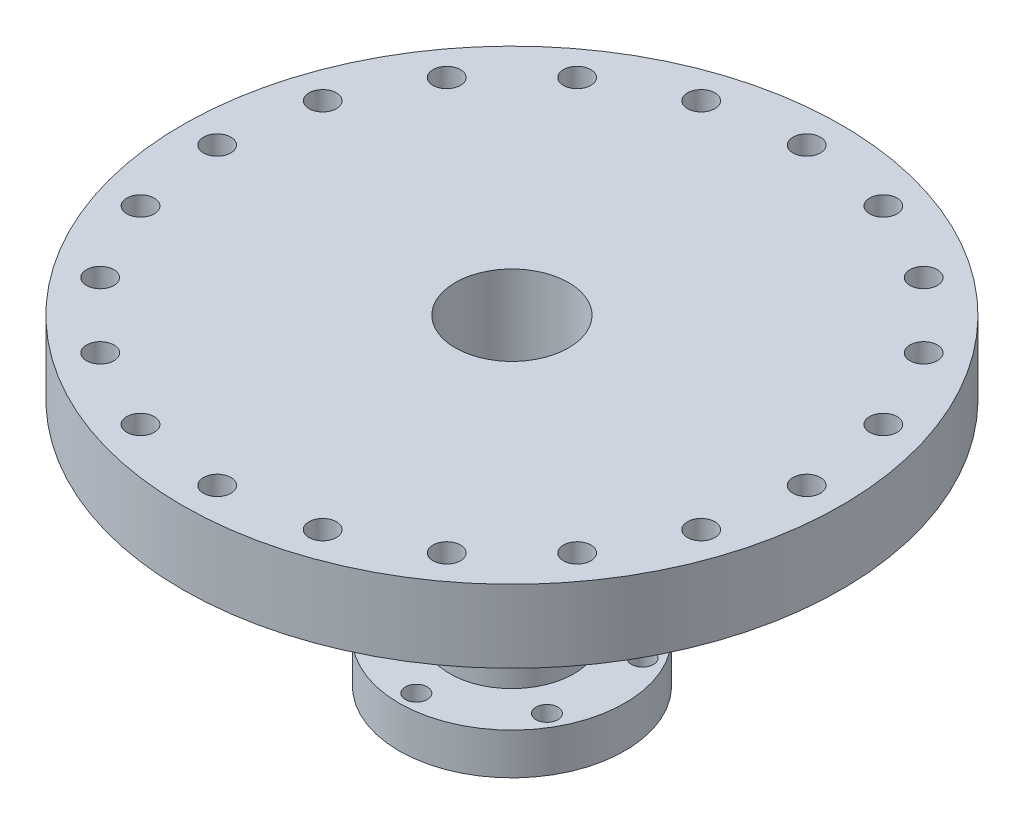
SolidWorks part; units mm, degrees
ref_plane "Front Plane" through (0, 0, 0) normal (0, 0, 1) x (1, 0, 0)
ref_plane "Top Plane" through (0, 0, 0) normal (0, 1, 0) x (1, 0, 0)
ref_plane "Right Plane" through (0, 0, 0) normal (1, 0, 0) x (0, 0, -1)
sketch "Sketch1" plane through (0, 0, 0) normal (0, 1, 0) x (1, 0, 0)
  circle A0 centre (0, 0) radius 19.05
  circle A1 centre (0, 0) radius 17.399
  dimension "D1" = 38.1
  dimension "D2" = 1.651
extrude "Extrude1" add sketch "Sketch1" along normal blind 63.5
sketch "Sketch2" plane through (0, 0, 0) normal (0, -1, 0) x (1, 0, 0)
  circle A0 centre (0, 0) radius 17.399
  circle A1 centre (0, 0) radius 34.671
  dimension "D1" = 69.342
extrude "Extrude2" add sketch "Sketch2" along normal blind 12.7
sketch "Sketch3" plane through (0, 63.5, 0) normal (0, 1, 0) x (1, 0, 0)
  circle A0 centre (0, 0) radius 17.399
  circle A1 centre (0, 0) radius 101.219
  dimension "D1" = 202.438
extrude "Extrude3" add sketch "Sketch3" along normal blind 22.352
sketch "Sketch4" plane through (0, 85.852, 0) normal (0, 1, 0) x (1, 0, 0)
  circle A0 centre (0, 90.5256) radius 4.2164
  dimension "D1" = 8.4328
  dimension "D2" = 90.5256
extrude "Extrude4" cut sketch "Sketch4" against normal up to next
pattern_circular "CirPattern1" count 20 over 360 about axis through (0, 0, 0) along (0, 1, 0) of "Extrude4"
sketch "Sketch6" plane through (0, -12.7, 0) normal (0, -1, 0) x (1, 0, 0)
  circle A0 centre (0, 29.3624) radius 3.3655
  dimension "D1" = 6.731
  dimension "D2" = 29.3624
extrude "Extrude5" cut sketch "Sketch6" against normal up to next
pattern_circular "CirPattern2" count 6 over 360 about axis through (0, 0, 0) along (0, 1, 0) of "Extrude5"
